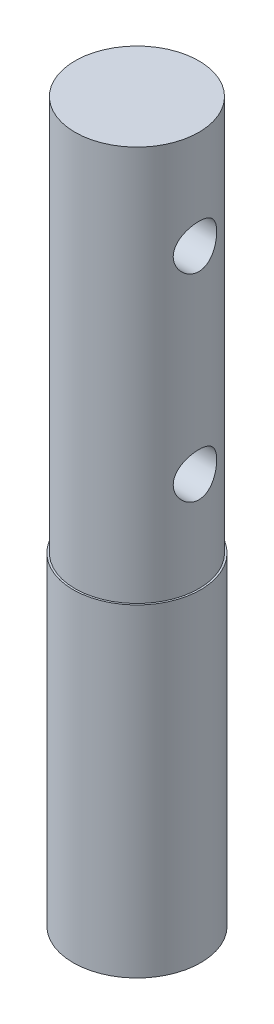
SolidWorks part; units mm, degrees
material "ASTM A36 Steel"
ref_plane "Front Plane" through (0, 0, 0) normal (0, 0, 1) x (1, 0, 0)
ref_plane "Top Plane" through (0, 0, 0) normal (0, 1, 0) x (1, 0, 0)
ref_plane "Right Plane" through (0, 0, 0) normal (1, 0, 0) x (0, 0, -1)
sketch "Sketch1" plane through (0, 0, 0) normal (0, 1, 0) x (1, 0, 0)
  circle A0 centre (0, 0) radius 32.25
  dimension "D1" = 64.5
extrude "Boss-Extrude1" add sketch "Sketch1" along normal blind 163.5
sketch "Sketch2" plane through (0, 163.5, 0) normal (0, 1, 0) x (1, 0, 0)
  circle A0 centre (0, 0) radius 31.34
  dimension "D1" = 62.68
extrude "Boss-Extrude2" add sketch "Sketch2" along normal blind 200
ref_plane "Plane1" through (25, 0, 0) normal (1, 0, 0) x (0, 0, -1)
sketch "Sketch3" plane through (0, 0, 0) normal (1, 0, 0) x (0, 0, -1)
  line L0 (32.25, 163.5) -> (-32.25, 163.5) construction
  circle A0 centre (0, 213.5) radius 11
  circle A1 centre (0, 313.5) radius 11
  dimension "D1" = 22
  dimension "D2" = 50
  dimension "D3" = 22
  dimension "D4" = 100
extrude "Cut-Extrude1" cut sketch "Sketch3" against normal through all both and the other way through all
